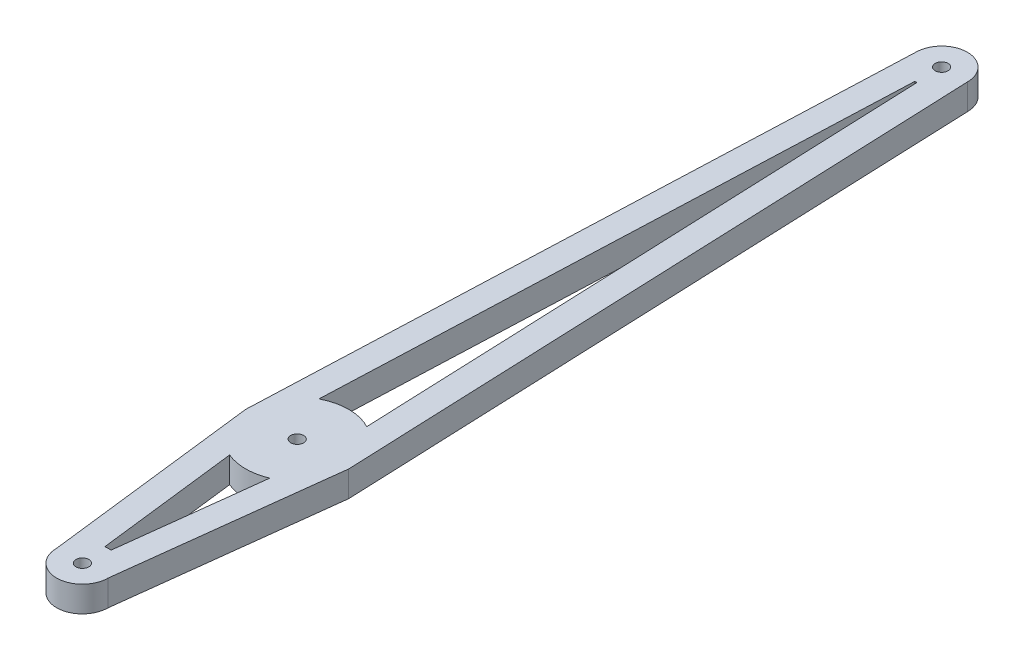
SolidWorks part; units mm, degrees
ref_plane "Front Plane" through (0, 0, 0) normal (0, 0, 1) x (1, 0, 0)
ref_plane "Top Plane" through (0, 0, 0) normal (0, 1, 0) x (1, 0, 0)
ref_plane "Right Plane" through (0, 0, 0) normal (1, 0, 0) x (0, 0, -1)
sketch "Sketch1" plane through (0, 0, 0) normal (0, 1, 0) x (1, 0, 0)
  line L0 (0, 0) -> (0, 150)
  line L1 (-12, 0) -> (-6, 150)
  line L2 (12, 0) -> (6, 150)
  line L3 (0, 150) -> (-6, 0)
  line L4 (0, 150) -> (6, 0)
  line L5 (0, 0) -> (0, -50)
  line L6 (-12, 0) -> (-6, -50)
  line L7 (-6, 0) -> (0, -50)
  line L8 (12, 0) -> (6, -50)
  line L9 (6, 0) -> (0, -50)
  circle A0 centre (0, 0) radius 12
  circle A1 centre (0, 150) radius 6
  circle A2 centre (0, 150) radius 1.5
  circle A3 centre (0, 0) radius 1.5
  circle A4 centre (0, -50) radius 1.5
  circle A5 centre (0, -50) radius 6
  dimension "D1" = 24
  dimension "D3" = 12
  dimension "D6" = 3
  dimension "D7" = 3
  dimension "D9" = 3
  dimension "D10" = 12
  dimension "D2" = 150
  dimension "D4" = 6
  dimension "D5" = 6
  dimension "D8" = 50
extrude "Boss-Extrude4" add sketch "Sketch1" along normal blind 6 contours A5 L8 A0 L9 | A5 L7 A0 L6 | L5 A5 L7 A4 | L9 A5 L5 A4 | A5 L9 A4 L7 | L9 A0 L8 L2 L4 | A3 L5 A0 L9 L4 L0 | A3 L0 A0 L3 L7 L5 | L3 A0 L1 L6 L7 | A1 L4 A0 L2 | A1 L1 A0 L3 | A2 L3 A1 L0 | A2 L4 A1 L3 | A2 L0 A1 L4
